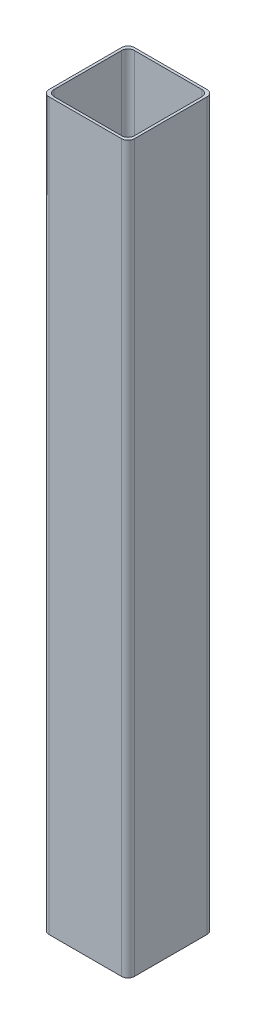
SolidWorks part; units mm, degrees
ref_plane "Plano frontal" through (0, 0, 0) normal (0, 0, 1) x (1, 0, 0)
ref_plane "Plano superior" through (0, 0, 0) normal (0, 1, 0) x (1, 0, 0)
ref_plane "Plano direito" through (0, 0, 0) normal (1, 0, 0) x (0, 0, -1)
sketch "Esboço1" plane through (0, 0, 0) normal (0, 1, 0) x (1, 0, 0)
  line L0 (-18.8, -18.8) -> (-18.8, 18.8)
  line L1 (20, -20) -> (-20, -20)
  line L2 (20, -20) -> (20, 20)
  line L3 (20, 20) -> (-20, 20)
  line L4 (-20, -20) -> (-20, 20)
  line L5 (20, -20) -> (-20, 20) construction
  line L6 (20, 20) -> (-20, -20) construction
  line L7 (18.8, 18.8) -> (-18.8, 18.8)
  line L8 (18.8, -18.8) -> (18.8, 18.8)
  line L9 (18.8, -18.8) -> (-18.8, -18.8)
  point P0 (0, 0)
  dimension "D1" = 40
  dimension "D2" = 40
  dimension "D3" = 1.2
extrude "Ressalto-extrusão1" add sketch "Esboço1" along normal mid plane 340
fillet "Filete1" radius 3 8 edges at (-20, 0, -20) (20, 0, -20) (18.8, 0, -18.8) (18.8, 0, 18.8) (-18.8, 0, 18.8) (-18.8, 0, -18.8) (-20, 0, 20) (20, 0, 20)
